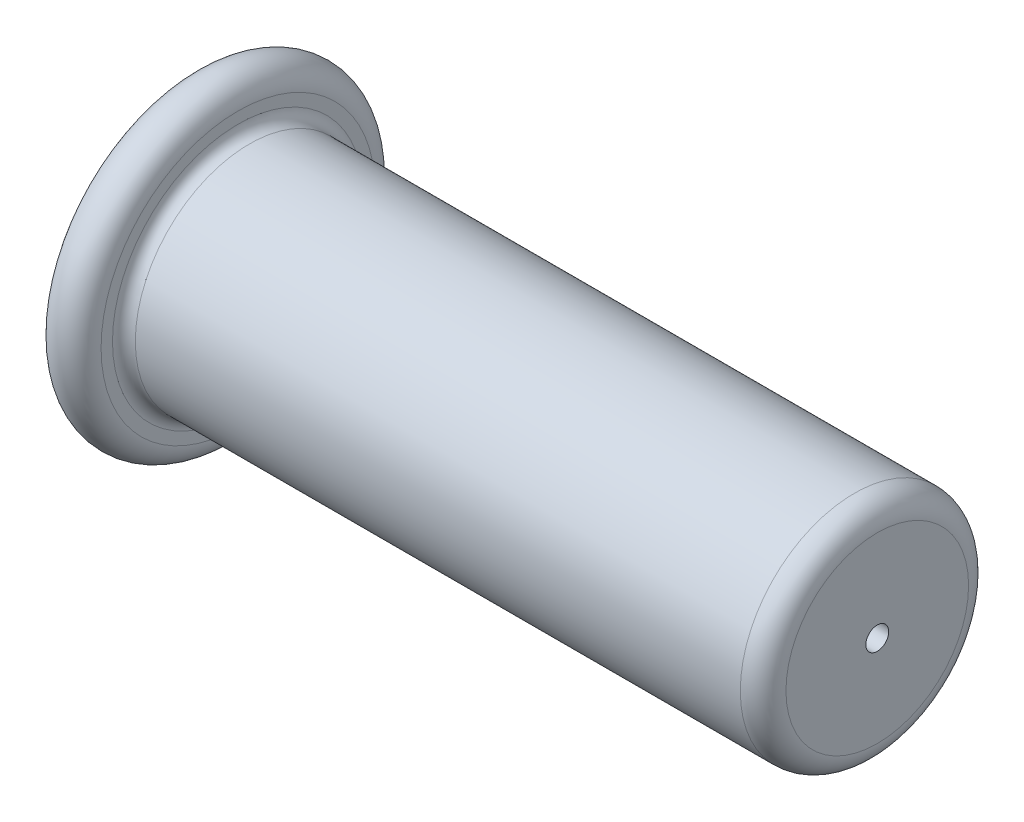
SolidWorks part; units mm, degrees
material "橡胶"
ref_plane "前视" through (0, 0, 0) normal (0, 0, 1) x (1, 0, 0)
ref_plane "上视" through (0, 0, 0) normal (0, 1, 0) x (1, 0, 0)
ref_plane "右视" through (0, 0, 0) normal (1, 0, 0) x (0, 0, -1)
sketch "草图1" plane through (0, 0, 0) normal (0, 0, 1) x (1, 0, 0)
  line L0 (0, 13) -> (0, 24)
  line L1 (0, 24) -> (8, 24) construction
  line L2 (8, 24) -> (8, 22)
  line L3 (120, 2) -> (120, 16)
  line L4 (116, 20) -> (10, 20)
  line L5 (120, 2) -> (117, 2)
  line L6 (1, 12) -> (60, 12)
  line L8 (0, 0) -> (71.2679, 0) construction
  line L9 (0, 0) -> (0, 62.3761) construction
  line L10 (117, 2) -> (60, 2)
  line L12 (60, 2) -> (60, 12)
  line L15 (1, 12) -> (0, 13)
  arc A0 (120, 16) -> (116, 20) centre (116, 16) ccw
  arc A1 (0, 24) -> (8, 24) centre (4, 24) cw
  arc A2 (8, 22) -> (10, 20) centre (10, 22) ccw
  point P11 (0, 12)
  dimension "D5" = 24
  dimension "D6" = 4
  dimension "D11" = 48
  dimension "D8" = 2
  dimension "D9" = 4
  dimension "D2" = 120
  dimension "D3" = 3
  dimension "D4" = 60
  dimension "D7" = 40
  dimension "D10" = 4
revolve "旋转1" add sketch "草图1" angle 360 about L8
